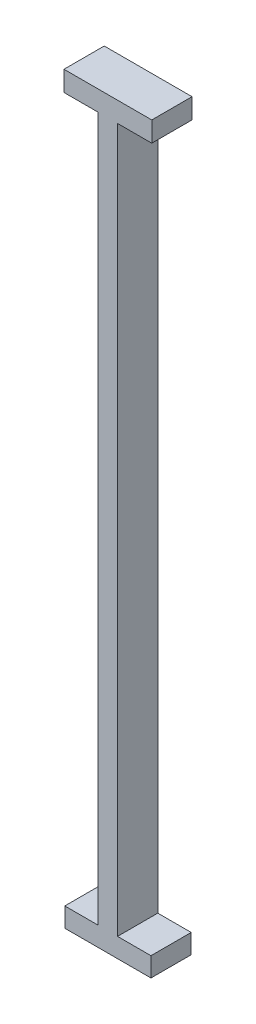
SolidWorks part; units mm, degrees
ref_plane "Front Plane" through (0, 0, 0) normal (0, 0, 1) x (1, 0, 0)
ref_plane "Top Plane" through (0, 0, 0) normal (0, 1, 0) x (1, 0, 0)
ref_plane "Right Plane" through (0, 0, 0) normal (1, 0, 0) x (0, 0, -1)
sketch "Sketch1" plane through (0, 0, 0) normal (0, 0, 1) x (1, 0, 0)
  line L1 (-11.1089, -1.8799) -> (10.2911, -1.8799)
  line L2 (-11.1089, -1.8799) -> (-11.1089, -6.6799)
  line L3 (-11.1089, -6.6799) -> (10.2911, -6.6799)
  line L4 (10.2911, -1.8799) -> (10.2911, -6.6799)
  line L9 (-2.8089, 0.4716) -> (1.9911, 0.4716)
  line L10 (-2.8089, 0.4716) -> (-2.8089, -1.8799)
  line L11 (-2.8089, -1.8799) -> (1.9911, -1.8799)
  line L12 (1.9911, 0.4716) -> (1.9911, -1.8799)
  dimension "D1" = 4.8
  dimension "D2" = 4.8
  dimension "D3" = 0
  dimension "D4" = 8.3
  dimension "D5" = 8.3
extrude "Boss-Extrude1" add sketch "Sketch1" along normal blind 10 contours L12 L9 L10 L1 | L4 L1 L2 L3
sketch "Sketch2" plane through (0, 0.4716, 0) normal (0, 1, 0) x (1, 0, 0)
  line L1 (-2.8089, 0) -> (1.9911, 0)
  line L2 (-2.8089, 0) -> (-2.8089, -10)
  line L3 (-2.8089, -10) -> (1.9911, -10)
  line L4 (1.9911, 0) -> (1.9911, -10)
extrude "Boss-Extrude2" add sketch "Sketch2" along normal blind 177.5
sketch "Sketch4" plane through (1.9911, 0, 0) normal (1, 0, 0) x (0, 0, -1)
  line L0 (0, 177.9716) -> (0, -1.8799) construction
  line L1 (-10, 177.9716) -> (0, 177.9716)
  line L2 (-10, 177.9716) -> (-10, 172.9716)
  line L3 (-10, 172.9716) -> (0, 172.9716)
  line L4 (0, 177.9716) -> (0, 172.9716)
  line L5 (-10, -1.8799) -> (0, -1.8799) construction
  line L6 (-10, -6.6799) -> (0, -6.6799) construction
  dimension "D1" = 5
  dimension "D2" = 4.8
extrude "Boss-Extrude6" add sketch "Sketch4" along normal blind 8.5 contours L2 L1 L4 L3
sketch "Sketch8" plane through (-2.8089, 0, 0) normal (-1, 0, 0) x (0, 0, 1)
  line L0 (10, 177.9716) -> (10, -1.8799) construction
  line L1 (0, 177.9716) -> (10, 177.9716)
  line L2 (0, 177.9716) -> (0, 172.9716)
  line L3 (0, 172.9716) -> (10, 172.9716)
  line L4 (10, 177.9716) -> (10, 172.9716)
  dimension "D1" = 5
extrude "Boss-Extrude7" add sketch "Sketch8" along normal blind 8.5
